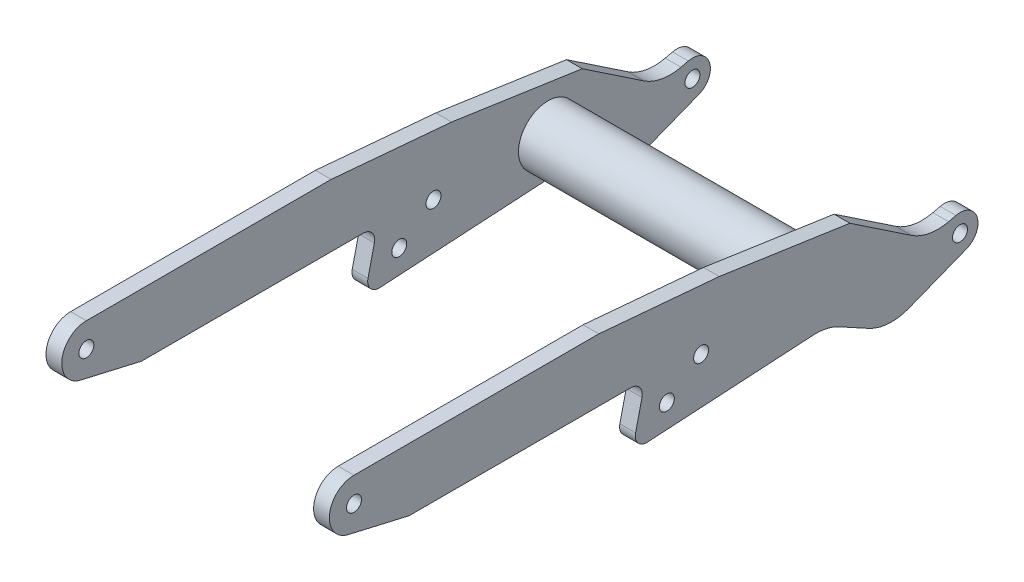
SolidWorks part; units mm, degrees
ref_plane "Front Plane" through (0, 0, 0) normal (0, 0, 1) x (1, 0, 0)
ref_plane "Top Plane" through (0, 0, 0) normal (0, 1, 0) x (1, 0, 0)
ref_plane "Right Plane" through (0, 0, 0) normal (1, 0, 0) x (0, 0, -1)
sketch "Sketch1" plane through (0, 0, 0) normal (1, 0, 0) x (0, 0, -1)
  line L0 (0, 0) -> (89.213, 0) construction
  line L1 (0, 3.13) -> (31.1, 3.13)
  line L2 (31.1, 3.13) -> (46.4, 1.7914)
  line L3 (46.4, 1.7914) -> (63, -0.6451)
  line L4 (63, -0.6451) -> (70.8261, -5.894)
  line L5 (76.4759, -6.5311) -> (75.5475, -6.7504)
  line L6 (-0.7041, -3.0498) -> (7, -4.8284)
  line L7 (7, -4.8284) -> (35.1753, -4.8284)
  line L8 (36.5879, -6.6059) -> (35.7778, -10.0997)
  line L9 (37.2759, -11.8747) -> (58.3825, -10.626)
  line L11 (61.6103, -11.3483) -> (65.4254, -13.4296)
  line L12 (70.4867, -13.7493) -> (77.8314, -10.873)
  circle A0 centre (0, 0) radius 0.95
  circle A1 centre (77, -8.75) radius 0.95
  circle A2 centre (39.75, -8.75) radius 0.95
  circle A3 centre (44.1, -5.6) radius 0.95
  arc A5 (0, 3.13) -> (-0.7041, -3.0498) centre (0, 0) ccw
  arc A7 (77.8314, -10.873) -> (76.4759, -6.5311) centre (77, -8.75) ccw
  arc A8 (58.3825, -10.626) -> (61.6103, -11.3483) centre (58.7369, -16.6155) cw
  arc A9 (70.8261, -5.894) -> (75.5475, -6.7504) centre (74.1682, -0.911) ccw
  arc A10 (65.4254, -13.4296) -> (70.4867, -13.7493) centre (68.2989, -8.1624) ccw
  arc A11 (35.1753, -4.8284) -> (36.5879, -6.6059) centre (35.1753, -6.2784) cw
  arc A12 (35.7778, -10.0997) -> (37.2759, -11.8747) centre (37.1903, -10.4273) ccw
  point P12 (77.7871, -10.8898)
  point P19 (60.1, -9.7122)
  point P24 (69.9786, -13.6061)
  point P25 (34.9274, -10.9035)
  point P28 (60.1, -10.5244)
  point P32 (73, -7.3521)
  point P35 (35.4252, -10.7932)
  point P36 (34.6704, -10.9512)
  point P37 (34.8792, -11.0099)
  point P38 (35.8229, -11.224)
  point P39 (35.796, -11.6846)
  point P40 (35.6161, -11.8955)
  point P43 (37, -4.8284)
  point P46 (35.7642, -9.4653)
  point P47 (35.5339, -9.8595)
  point P48 (58.4053, -10.7646)
  point P49 (35.7106, -11.0204)
  point P50 (35.7778, -10.0997)
  dimension "D1" = 1.9
  dimension "D8" = 3.13
  dimension "D9" = 175
  dimension "D16" = 2.28
  dimension "D24" = 6
  dimension "D20" = 1.45
  dimension "D2" = 39.75
  dimension "D3" = 8.75
  dimension "D4" = 44.1
  dimension "D5" = 5.6
  dimension "D6" = 77
  dimension "D7" = 8.75
  dimension "D10" = 31.1
  dimension "D11" = 46.4
  dimension "D12" = 63
  dimension "D13" = 10
  dimension "D14" = 176.65
  dimension "D15" = 154.5
  dimension "D17" = 7
  dimension "D18" = 167
  dimension "D19" = 30
  dimension "D21" = 16
  dimension "D22" = 148
  dimension "D23" = 130
  dimension "D25" = 73.56
extrude "Boss-Extrude1" add sketch "Sketch1" along normal mid plane 36
sketch "Sketch2" plane through (0, 0, 0) normal (0, 1, 0) x (1, 0, 0)
  line L0 (-18, -3.13) -> (18, -3.13) construction
  line L1 (-16, -3.13) -> (16, -3.13)
  line L2 (-16, -3.13) -> (-16, 79.28)
  line L3 (-16, 79.28) -> (16, 79.28)
  line L4 (16, -3.13) -> (16, 79.28)
  line L7 (18, 79.28) -> (-18, 79.28) construction
  line L8 (18, 63) -> (18, 46.4) construction
  line L9 (-18, 63) -> (-18, 46.4) construction
  point P13 (0, 0)
  dimension "D1" = 2
  dimension "D2" = 2
extrude "Cut-Extrude1" cut sketch "Sketch2" against normal mid plane 36
sketch "Sketch3" plane through (18, 0, 0) normal (1, 0, 0) x (0, 0, -1)
  circle A0 centre (58.65, -5.75) radius 3.75
  point P5 (32.6221, 7.2538)
  dimension "D1" = 7.5
  dimension "D2" = 58.65
  dimension "D3" = 5.75
extrude "Boss-Extrude2" add sketch "Sketch3" against normal up to surface (34 mm away) up to face at (-16, 0, 0.95)
